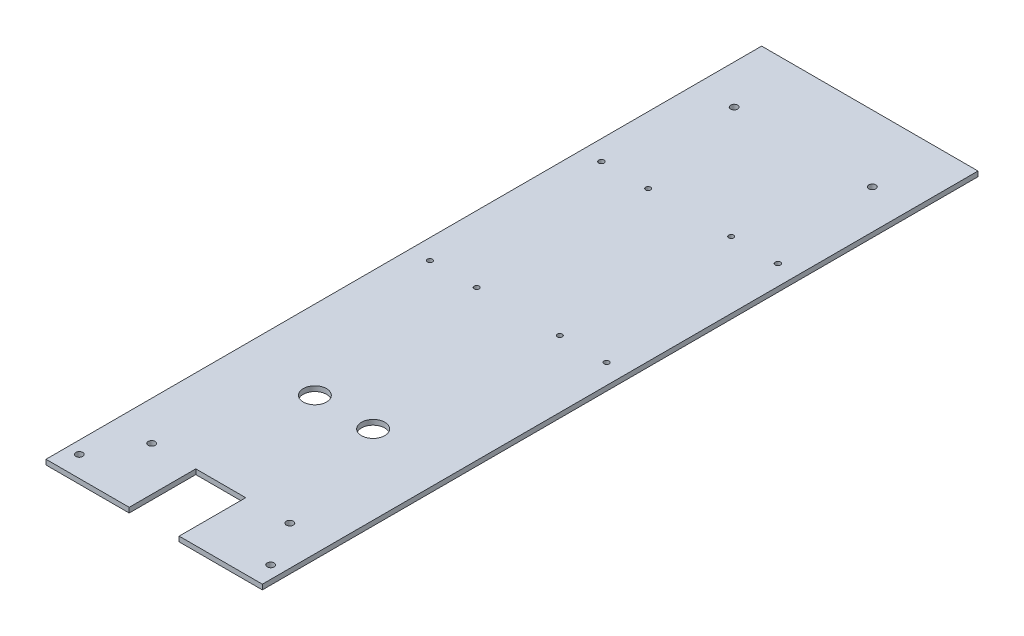
SolidWorks part; units mm, degrees
ref_plane "Front Plane" through (0, 0, 0) normal (0, 0, 1) x (1, 0, 0)
ref_plane "Top Plane" through (0, 0, 0) normal (0, 1, 0) x (1, 0, 0)
ref_plane "Right Plane" through (0, 0, 0) normal (1, 0, 0) x (0, 0, -1)
sketch "Sketch1" plane through (0, 0, 0) normal (0, 1, 0) x (1, 0, 0)
  line L1 (-65, 215) -> (65, 215)
  line L2 (-65, 215) -> (-65, -215)
  line L3 (-65, -215) -> (65, -215)
  line L4 (65, 215) -> (65, -215)
  line L5 (-65, 215) -> (65, -215) construction
  line L6 (-65, -215) -> (65, 215) construction
  point P0 (0, 0)
  dimension "D1" = 130
  dimension "D2" = 430
extrude "Boss-Extrude1" add sketch "Sketch1" along normal blind 3
sketch "Sketch2" plane through (0, 3, 0) normal (0, 1, 0) x (1, 0, 0)
  line L0 (-65, -215) -> (65, -215) construction
  line L1 (15, -215) -> (-15, -215)
  line L2 (15, -215) -> (15, -175)
  line L3 (15, -175) -> (-15, -175)
  line L4 (-15, -215) -> (-15, -175)
  line L5 (33, -215) -> (33, 215) construction
  line L6 (-33, -215) -> (-33, 215) construction
  dimension "D3" = 0
  dimension "D1" = 18
  dimension "D2" = 18
  dimension "D4" = 40
extrude "Cut-Extrude1" cut sketch "Sketch2" against normal blind 10 contours L2 L3 L4 L1
sketch "Sketch3" plane through (0, 0, 0) normal (0, -1, 0) x (1, 0, 0)
  line L0 (0, 33.6472) -> (0, -145.4342) construction
  line L1 (-65, -215) -> (-65, 215) construction
  circle A0 centre (-53.05, -3.75) radius 1.5
  circle A2 centre (-24.95, -3.75) radius 1.5
  circle A3 centre (-53.05, -106.75) radius 1.6
  circle A5 centre (-24.95, -106.75) radius 1.5
  circle A6 centre (24.95, -106.75) radius 1.5
  circle A7 centre (57.5, 202.5) radius 2.1
  circle A8 centre (53.05, -106.75) radius 1.6
  circle A9 centre (24.95, -3.75) radius 1.5
  circle A10 centre (-57.5, 202.5) radius 2.1
  circle A11 centre (53.05, -3.75) radius 1.5
  circle A12 centre (-41.5, 175) radius 2.1
  circle A13 centre (41.5, 175) radius 2.1
  circle A14 centre (41.5, -175) radius 2.1
  circle A15 centre (-41.5, -175) radius 2.1
  dimension "D1" = 3.2
  dimension "D4" = 4.2
  dimension "D5" = 4.2
  dimension "D2" = 65
extrude "Cut-Extrude2" cut sketch "Sketch3" against normal blind 10
sketch "Sketch4" plane through (0, 0, 0) normal (0, -1, 0) x (1, 0, 0)
  line L0 (-65, -215) -> (-65, 215) construction
  circle A0 centre (-17.5, 100.9522) radius 7
  circle A1 centre (17.5, 100.9522) radius 7
  dimension "D1" = 35
  dimension "D2" = 47.5
  dimension "D3" = 14
  dimension "D4" = 14
extrude "Cut-Extrude3" cut sketch "Sketch4" against normal blind 10
